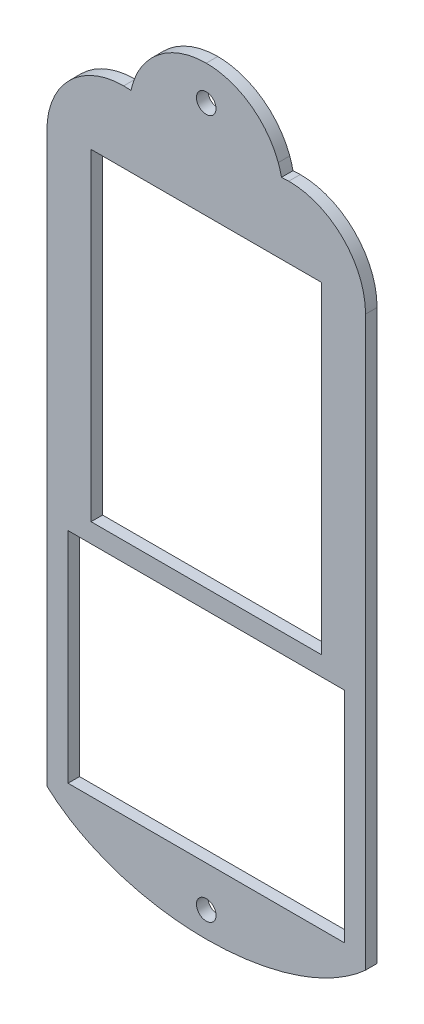
SolidWorks part; units mm, degrees
ref_plane "前视基准面" through (0, 0, 0) normal (0, 0, 1) x (1, 0, 0)
ref_plane "上视基准面" through (0, 0, 0) normal (0, 1, 0) x (1, 0, 0)
ref_plane "右视基准面" through (0, 0, 0) normal (1, 0, 0) x (0, 0, -1)
other "Configuration Table"
sketch "草图1" plane through (0, 0, 0) normal (0, 0, 1) x (1, 0, 0)
  line L0 (-84.75, 68.1509) -> (-84.75, -79.8491)
  line L1 (-1.7484, 68.1509) -> (-1.7484, -79.8491)
  line L2 (-4.2492, 72.5719) -> (-11.3961, 72.5719) construction
  line L3 (-73.2492, 69.5719) -> (-13.2492, 69.5719)
  line L4 (-73.2492, 69.5719) -> (-73.2492, -14.4281)
  line L5 (-73.2492, -14.4281) -> (-13.2492, -14.4281)
  line L6 (-13.2492, 69.5719) -> (-13.2492, -14.4281)
  line L7 (-4.2492, 34.32) -> (-4.2492, 65.5798) construction
  line L8 (-82.2492, 65.5798) -> (-82.2492, 45.884) construction
  line L9 (-4.2492, -36.128) -> (-4.2492, -61.3032) construction
  line L10 (-79.2492, -19.4281) -> (-7.2492, -19.4281)
  line L11 (-79.2492, -19.4281) -> (-79.2492, -76.4281)
  line L12 (-79.2492, -76.4281) -> (-7.2492, -76.4281)
  line L13 (-7.2492, -19.4281) -> (-7.2492, -76.4281)
  line L14 (-7.8227, -79.4281) -> (-4.2492, -79.4281) construction
  line L15 (-82.2492, -52.8839) -> (-82.2492, -72.0269) construction
  circle A0 centre (-43.2492, 95.0101) radius 2.55
  circle A1 centre (-43.2492, -86.9899) radius 2.55
  spline S0 degree 3 poles (-1.7484, 68.1509) (-1.7484, 79.1964) (-10.7019, 88.1499) (-21.7474, 88.1499) knots 0 0 0 0 1 1 1 1
  spline S1 degree 3 poles (-21.7474, 88.1499) (-22.3894, 88.1499) (-23.028, 88.1181) (-23.6559, 88.0581) knots 1 1 1 1 2 2 2 2
  spline S2 degree 3 poles (-23.6559, 88.0581) (-23.8605, 89.0565) (-24.1427, 90.0302) (-24.4885, 90.9721) knots 2 2 2 2 3 3 3 3
  spline S3 degree 3 poles (-24.4885, 90.9721) (-27.3107, 98.5921) (-34.6449, 104.0249) (-43.2492, 104.0249) knots 3 3 3 3 4 4 4 4
  spline S4 degree 3 poles (-43.2492, 104.0249) (-51.8534, 104.0249) (-59.1877, 98.5921) (-62.0099, 90.9721) knots 4 4 4 4 5 5 5 5
  spline S5 degree 3 poles (-62.0099, 90.9721) (-62.3556, 90.0302) (-62.6379, 89.0565) (-62.8425, 88.0581) knots 5 5 5 5 6 6 6 6
  spline S6 degree 3 poles (-62.8425, 88.0581) (-63.4704, 88.1181) (-64.1054, 88.1499) (-64.7475, 88.1499) knots 6 6 6 6 7 7 7 7
  spline S7 degree 3 poles (-64.7475, 88.1499) (-75.7965, 88.1499) (-84.75, 79.1964) (-84.75, 68.1509) knots 7 7 7 7 8 8 8 8
  spline S8 degree 3 poles (-84.75, -79.8491) (-81.6385, -82.6925) (-77.8179, -85.1972) (-73.447, -87.268) knots 11 11 11 11 12 12 12 12
  spline S9 degree 3 poles (-73.447, -87.268) (-65.0297, -91.2579) (-54.5733, -93.618) (-43.2492, -93.618) knots 12 12 12 12 13 13 13 13
  spline S10 degree 3 poles (-43.2492, -93.618) (-31.925, -93.618) (-21.4687, -91.2579) (-13.0514, -87.268) knots 13 13 13 13 14 14 14 14
  spline S11 degree 3 poles (-13.0514, -87.268) (-8.6805, -85.1972) (-4.8599, -82.6925) (-1.7484, -79.8491) knots 14 14 14 14 15 15 15 15
  dimension "D1" = 3
  dimension "D2" = 9
  dimension "D3" = 9
  dimension "D4" = 5
  dimension "D5" = 3
  dimension "D6" = 3
  dimension "D7" = 3
extrude "凸台-拉伸1" add sketch "草图1" along normal blind 3
